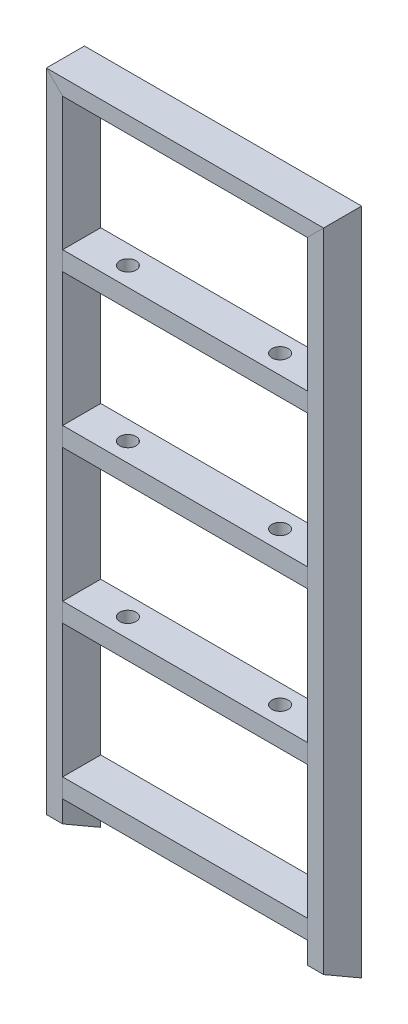
SolidWorks part; units mm, degrees
ref_plane "Front Plane" through (0, 0, 0) normal (0, 0, 1) x (1, 0, 0)
ref_plane "Top Plane" through (0, 0, 0) normal (0, 1, 0) x (1, 0, 0)
ref_plane "Right Plane" through (0, 0, 0) normal (1, 0, 0) x (0, 0, -1)
sketch "Sketch2" plane through (0, 0, 0) normal (0, 0, 1) x (1, 0, 0)
  line L1 (-304.8, 0) -> (304.8, 0)
  line L2 (-304.8, 0) -> (-304.8, -1524)
  line L3 (-304.8, -1524) -> (304.8, -1524)
  line L4 (304.8, 0) -> (304.8, -1524)
  dimension "D1" = 609.6
  dimension "D2" = 1524
sketch "Sketch3" plane through (0, 0, 0) normal (0, 1, 0) x (1, 0, 0)
  line L1 (285.75, 44.45) -> (323.85, 44.45)
  line L2 (285.75, 44.45) -> (285.75, -44.45)
  line L3 (285.75, -44.45) -> (323.85, -44.45)
  line L4 (323.85, 44.45) -> (323.85, -44.45)
  line L5 (285.75, 44.45) -> (323.85, -44.45) construction
  line L6 (285.75, -44.45) -> (323.85, 44.45) construction
  point P0 (304.8, 0)
  dimension "D1" = 38.1
  dimension "D2" = 88.9
sweep "Sweep1" add profiles "Sketch3" path "Sketch2"
sketch "Sketch10" plane through (0, 0, 44.45) normal (0, 0, 1) x (1, 0, 0)
  line L0 (-285.75, -1504.95) -> (-285.75, -19.05) construction
  line L1 (-285.75, -1469.7317) -> (285.75, -1469.7317)
  line L2 (-285.75, -1469.7317) -> (-285.75, -1653.1251)
  line L3 (-285.75, -1653.1251) -> (285.75, -1653.1251)
  line L4 (285.75, -1469.7317) -> (285.75, -1653.1251)
  line L5 (285.75, -19.05) -> (285.75, -1504.95) construction
extrude "Cut-Extrude6" cut sketch "Sketch10" against normal through all
sketch "Sketch9" plane through (323.85, 0, 0) normal (1, 0, 0) x (0, 0, -1)
  line L0 (44.45, -1543.05) -> (-44.45, -1491.7236)
  line L1 (-44.45, 19.05) -> (-44.45, -1543.05) construction
  line L2 (44.45, 19.05) -> (44.45, -1543.05) construction
  line L3 (44.45, -1543.05) -> (-44.45, -1543.05) construction
  dimension "D1" = 120
  dimension "D2" = 0
extrude "Cut-Extrude7" cut sketch "Sketch9" against normal through all both and the other way through all
sketch "Sketch11" plane through (285.75, 0, 0) normal (-1, 0, 0) x (0, 0, 1)
  line L0 (44.45, -19.05) -> (44.45, -1491.7236) construction
  line L1 (44.45, -1440.9236) -> (-44.45, -1440.9236)
  line L2 (44.45, -1440.9236) -> (44.45, -1396.4736)
  line L3 (44.45, -1396.4736) -> (-44.45, -1396.4736)
  line L4 (-44.45, -1440.9236) -> (-44.45, -1396.4736)
  line L5 (-44.45, -19.05) -> (-44.45, -1504.95) construction
  dimension "D1" = 44.45
  dimension "D2" = 50.8
extrude "Boss-Extrude1" add sketch "Sketch11" along normal up to surface (571.5 mm away) separate body up to face at (-285.75, -915.5647, -8.89)
pattern_linear "LPattern1" count 4 spacing 355.6 along (0, 1, 0) of "Boss-Extrude1"
sketch "Sketch12" plane through (0, -1085.3236, 0) normal (0, -1, 0) x (1, 0, 0)
  line L0 (-177.8, 0) -> (0, 0) construction
  line L1 (0, 0) -> (177.8, 0) construction
  circle A0 centre (177.8, 0) radius 19.05
  circle A1 centre (-177.8, 0) radius 19.05
  dimension "D2" = 38.1
  dimension "D1" = 177.8
extrude "Cut-Extrude8" cut sketch "Sketch12" against normal blind 990.6
